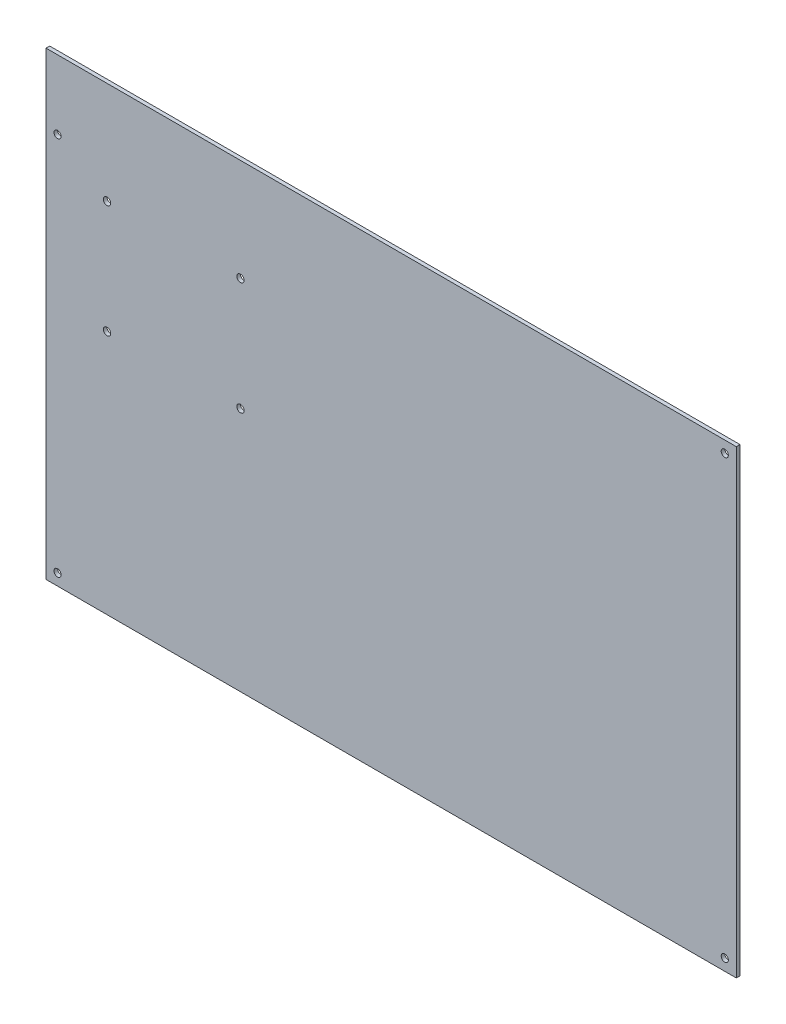
SolidWorks part; units mm, degrees
ref_plane "正面" through (0, 0, 0) normal (0, 0, 1) x (1, 0, 0)
ref_plane "平面" through (0, 0, 0) normal (0, 1, 0) x (1, 0, 0)
ref_plane "右側面" through (0, 0, 0) normal (1, 0, 0) x (0, 0, -1)
sketch "ｽｹｯﾁ1" plane through (0, 0, 0) normal (0, 0, 1) x (1, 0, 0)
  line L1 (-150, -100) -> (150, -100)
  line L2 (-150, -100) -> (-150, 100)
  line L3 (-150, 100) -> (150, 100)
  line L4 (150, -100) -> (150, 100)
  line L5 (-150, -100) -> (150, 100) construction
  line L6 (-150, 100) -> (150, -100) construction
  line L7 (-145, 95) -> (145, 95) construction
  line L8 (-145, 95) -> (-145, -95) construction
  line L9 (-145, -95) -> (145, -95) construction
  line L10 (145, 95) -> (145, -95) construction
  line L11 (-145, 95) -> (145, -95) construction
  line L12 (-145, -95) -> (145, 95) construction
  circle A1 centre (-145, -95) radius 1.55
  circle A2 centre (145, 95) radius 1.55
  circle A3 centre (145, -95) radius 1.55
  circle A4 centre (-145, 70) radius 1.55
  point P0 (0, 0)
  point P5 (0, 0)
  dimension "D5" = 3.1
  dimension "D6" = 170
  dimension "D1" = 300
  dimension "D2" = 200
  dimension "D3" = 5
  dimension "D4" = 5
extrude "ﾎﾞｽ - 押し出し1" add sketch "ｽｹｯﾁ1" along normal blind 1.6
sketch "ｽｹｯﾁ2" plane through (0, 0, 1.6) normal (0, 0, 1) x (1, 0, 0)
  line L0 (-150, 100) -> (-150, -100) construction
  line L1 (-65.5, 6.6) -> (-123.5, 6.6) construction
  line L2 (-65.5, 6.6) -> (-65.5, 55.6) construction
  line L3 (-65.5, 55.6) -> (-123.5, 55.6) construction
  line L4 (-123.5, 6.6) -> (-123.5, 55.6) construction
  line L5 (-65.5, 6.6) -> (-123.5, 55.6) construction
  line L6 (-65.5, 55.6) -> (-123.5, 6.6) construction
  line L7 (-150, -100) -> (150, -100) construction
  circle A0 centre (-123.5, 55.6) radius 1.6
  circle A1 centre (-65.5, 55.6) radius 1.6
  circle A2 centre (-123.5, 6.6) radius 1.6
  circle A3 centre (-65.5, 6.6) radius 1.6
  point P0 (-94.5, 31.1)
  dimension "D1" = 26.5
  dimension "D2" = 3.2
  dimension "D4" = 58
  dimension "D3" = 155.6
  dimension "D5" = 49
extrude "ｶｯﾄ - 押し出し1" cut sketch "ｽｹｯﾁ2" against normal through all
